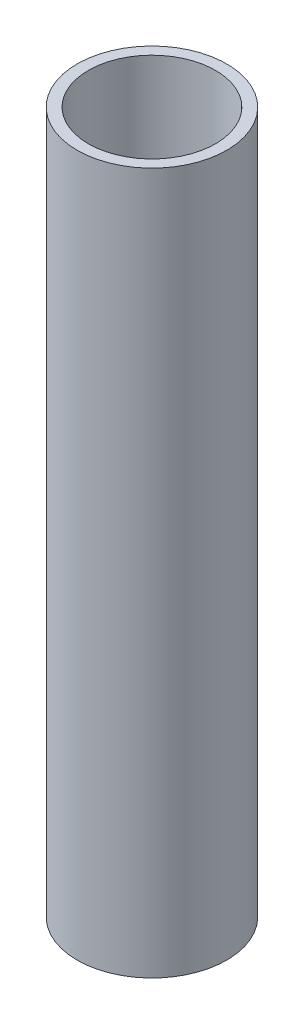
SolidWorks part; units mm, degrees
ref_plane "前视基准面" through (0, 0, 0) normal (0, 0, 1) x (1, 0, 0)
ref_plane "上视基准面" through (0, 0, 0) normal (0, 1, 0) x (1, 0, 0)
ref_plane "右视基准面" through (0, 0, 0) normal (1, 0, 0) x (0, 0, -1)
other "Configuration Table"
sketch "草图1" plane through (0, 0, 0) normal (0, 1, 0) x (1, 0, 0)
  circle A14 centre (0, 0) radius 16
  circle A15 centre (0, 0) radius 13.6
  dimension "D1" = 32
  dimension "D2" = 2.4
extrude "凸台-拉伸1" add sketch "草图1" along normal blind 150
